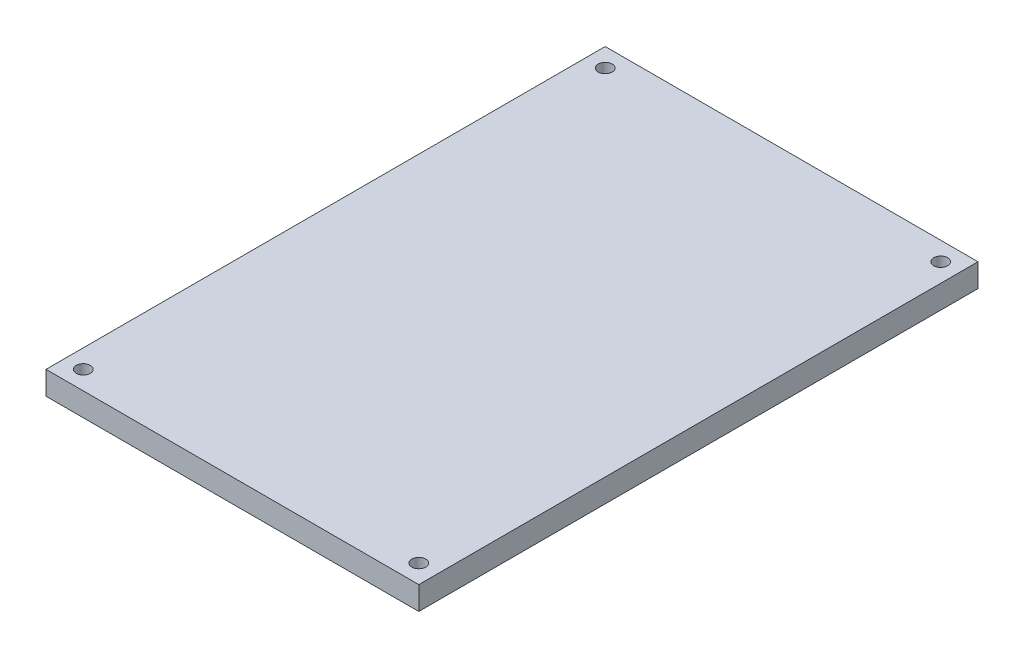
SolidWorks part; units mm, degrees
ref_plane "Front Plane" through (0, 0, 0) normal (0, 0, 1) x (1, 0, 0)
ref_plane "Top Plane" through (0, 0, 0) normal (0, 1, 0) x (1, 0, 0)
ref_plane "Right Plane" through (0, 0, 0) normal (1, 0, 0) x (0, 0, -1)
sketch "Sketch1" plane through (0, 0, 0) normal (0, 1, 0) x (1, 0, 0)
  line L1 (0, 0) -> (-80, 0)
  line L2 (0, 0) -> (0, 120)
  line L3 (0, 120) -> (-80, 120)
  line L4 (-80, 0) -> (-80, 120)
  dimension "D1" = 120
  dimension "D2" = 80
extrude "Boss-Extrude1" add sketch "Sketch1" along normal blind 5
sketch "Sketch2" plane through (0, 5, 0) normal (0, 1, 0) x (1, 0, 0)
  line L0 (0, 120) -> (-80, 120) construction
  line L1 (-80, 120) -> (-80, 0) construction
  circle A0 centre (-76, 116) radius 1.5
  dimension "D1" = 3
  dimension "D2" = 4
  dimension "D3" = 4
extrude "Cut-Extrude1" cut sketch "Sketch2" against normal through all
sketch "Sketch3" plane through (0, 5, 0) normal (0, 1, 0) x (1, 0, 0)
  line L0 (0, 0) -> (0, 120) construction
  line L1 (0, 120) -> (-80, 120) construction
  circle A0 centre (-4, 116) radius 1.5
  dimension "D1" = 3
  dimension "D2" = 4
  dimension "D3" = 4
extrude "Cut-Extrude2" cut sketch "Sketch3" against normal through all
ref_plane "Plane1" through (0, 0, -60) normal (0, 0, 1) x (1, 0, 0)
mirror "Mirror1" about plane through (0, 0, -60) normal (0, 0, 1) of "Cut-Extrude2", "Cut-Extrude1"
